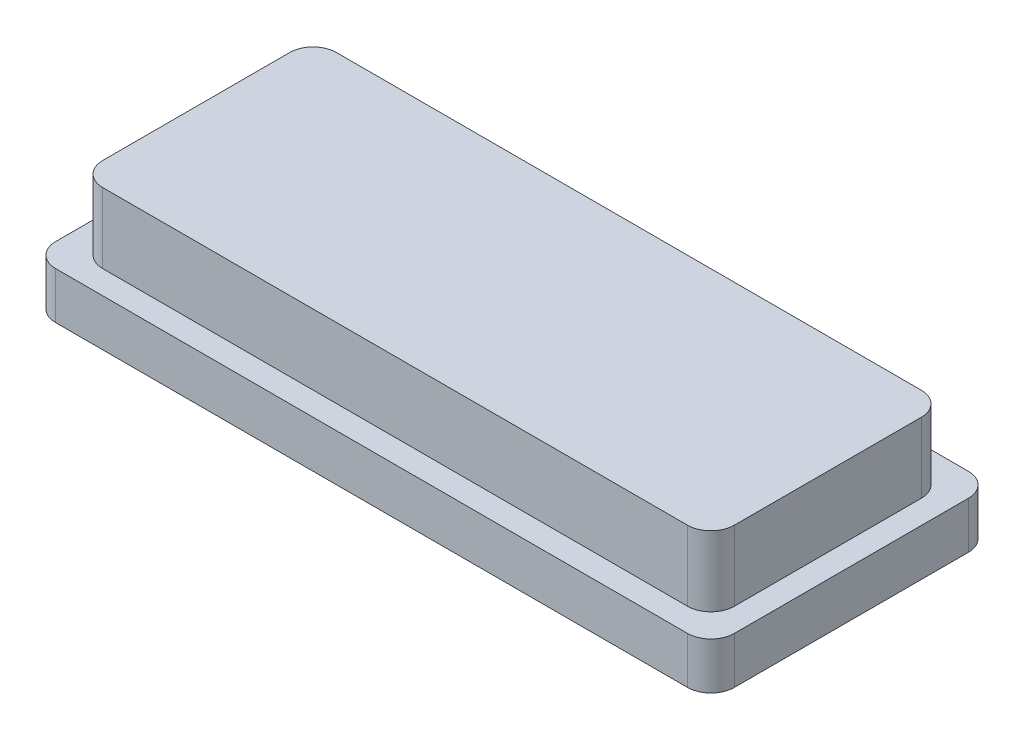
SolidWorks part; units mm, degrees
ref_plane "Front Plane" through (0, 0, 0) normal (0, 0, 1) x (1, 0, 0)
ref_plane "Top Plane" through (0, 0, 0) normal (0, 1, 0) x (1, 0, 0)
ref_plane "Right Plane" through (0, 0, 0) normal (1, 0, 0) x (0, 0, -1)
sketch "Sketch1" plane through (0, 0, 0) normal (0, 1, 0) x (1, 0, 0)
  line L1 (-13.5, 6) -> (13.5, 6)
  line L2 (-14.5, 5) -> (-14.5, -5)
  line L3 (-13.5, -6) -> (13.5, -6)
  line L4 (14.5, 5) -> (14.5, -5)
  line L5 (-14.5, 6) -> (14.5, -6) construction
  line L6 (-14.5, -6) -> (14.5, 6) construction
  arc A0 (14.5, 5) -> (13.5, 6) centre (13.5, 5) ccw
  arc A1 (13.5, -6) -> (14.5, -5) centre (13.5, -5) ccw
  arc A2 (-14.5, 5) -> (-13.5, 6) centre (-13.5, 5) cw
  arc A3 (-13.5, -6) -> (-14.5, -5) centre (-13.5, -5) cw
  point P0 (0, 0)
  dimension "D3" = 1
  dimension "D4" = 1
  dimension "D5" = 1
  dimension "D6" = 1
  dimension "D1" = 29
  dimension "D2" = 12
extrude "Boss-Extrude1" add sketch "Sketch1" along normal blind 2
sketch "Sketch2" plane through (0, 2, 0) normal (0, 1, 0) x (1, 0, 0)
  line L1 (-12.495, 4.995) -> (12.495, 4.995)
  line L2 (-13.495, 3.995) -> (-13.495, -3.995)
  line L3 (-12.495, -4.995) -> (12.495, -4.995)
  line L4 (13.495, 3.995) -> (13.495, -3.995)
  line L5 (-13.495, 4.995) -> (13.495, -4.995) construction
  line L6 (-13.495, -4.995) -> (13.495, 4.995) construction
  arc A0 (-13.495, 3.995) -> (-12.495, 4.995) centre (-12.495, 3.995) cw
  arc A1 (13.495, 3.995) -> (12.495, 4.995) centre (12.495, 3.995) ccw
  arc A2 (-12.495, -4.995) -> (-13.495, -3.995) centre (-12.495, -3.995) cw
  arc A3 (12.495, -4.995) -> (13.495, -3.995) centre (12.495, -3.995) ccw
  point P0 (0, 0)
  dimension "D3" = 1
  dimension "D4" = 1
  dimension "D5" = 1
  dimension "D6" = 1
  dimension "D1" = 26.99
  dimension "D2" = 9.99
extrude "Boss-Extrude2" add sketch "Sketch2" along normal blind 3 contours A3 L3 A2 L2 A0 L1 A1 L4
